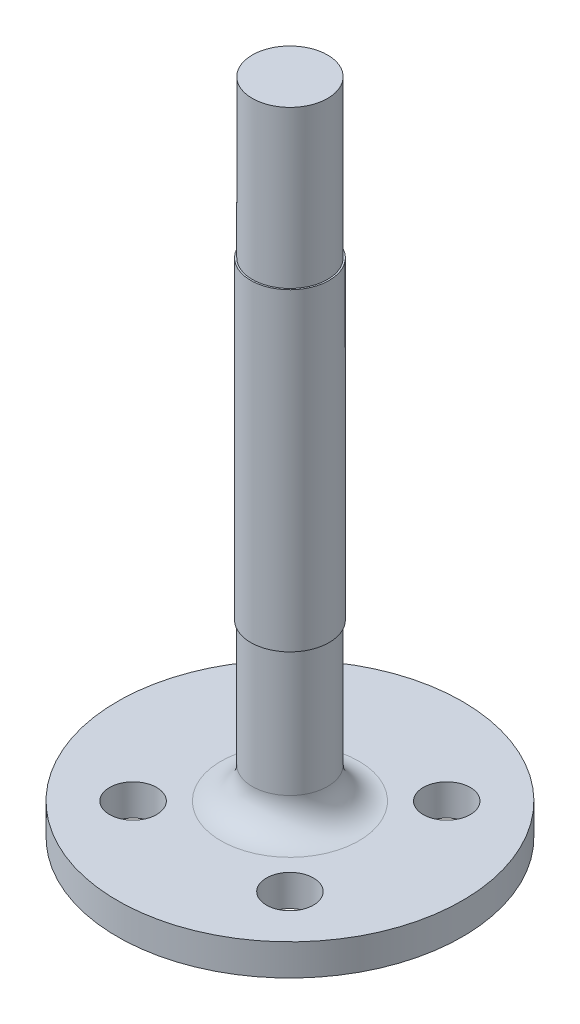
SolidWorks part; units mm, degrees
ref_plane "前视基准面" through (0, 0, 0) normal (0, 0, 1) x (1, 0, 0)
ref_plane "上视基准面" through (0, 0, 0) normal (0, 1, 0) x (1, 0, 0)
ref_plane "右视基准面" through (0, 0, 0) normal (1, 0, 0) x (0, 0, -1)
other "Configuration Table"
sketch "草图1" plane through (0, 0, 0) normal (0, 1, 0) x (1, 0, 0)
  circle A0 centre (0, 0) radius 2.4
  dimension "D1" = 4.8
extrude "凸台-拉伸1" add sketch "草图1" along normal blind 40
ref_plane "基准面1" through (0, 20, 0) normal (0, -1, 0) x (-1, 0, 0)
sketch "草图2" plane through (0, 20, 0) normal (0, -1, 0) x (-1, 0, 0)
  circle A0 centre (0, 0) radius 2.5
  dimension "D1" = 5
extrude "凸台-拉伸2" add sketch "草图2" along normal mid plane 20
sketch "草图3" plane through (0, 0, 0) normal (0, -1, 0) x (1, 0, 0)
  line L1 (-5, -5) -> (5, -5)
  line L2 (-5, -5) -> (-5, 5)
  line L3 (-5, 5) -> (5, 5)
  line L4 (5, -5) -> (5, 5)
  line L5 (-5, -5) -> (5, 5) construction
  line L6 (-5, 5) -> (5, -5) construction
  circle A0 centre (0, 0) radius 11
  circle A1 centre (-5, 5) radius 1.5
  circle A2 centre (5, 5) radius 1.5
  circle A3 centre (5, -5) radius 1.5
  circle A4 centre (-5, -5) radius 1.5
  circle M3 centre (0, 0) radius 2.4
  dimension "D1" = 22
  dimension "D4" = 3
  dimension "D2" = 10
  dimension "D3" = 10
  dimension "D5" = 4
extrude "凸台-拉伸3" add sketch "草图3" along normal blind 2 separate body contours A0 A4 L2 A1 L3 A2 L4 A3 L1 | A4 L1 A3 L4 A2 L3 A1 L2 M3
sketch "草图4" plane through (0, 0, 0) normal (1, 0, 0) x (0, 0, -1)
  line L0 (-2.4, 0) -> (-4.4, 0)
  line L3 (-3.5, 0) -> (-6.5, 0) construction
  line L4 (-2.4, 10) -> (-2.4, 0) construction
  line L5 (-2.4, 2) -> (-2.4, 0)
  line L6 (0, -1000) -> (0, 49000) construction
  arc A1 (-4.4, 0) -> (-2.4, 2) centre (-4.4, 2) ccw
  dimension "D1" = 2
revolve "旋转3" add sketch "草图4" angle 360 about L6
